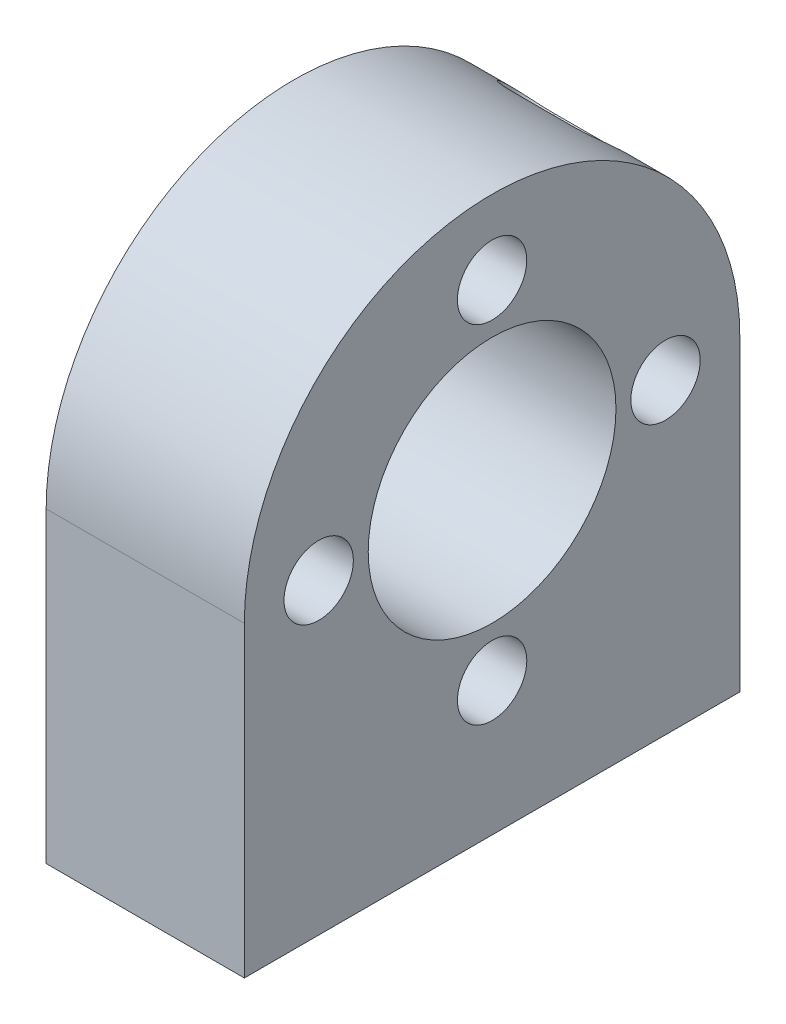
SolidWorks part; units mm, degrees
ref_plane "Ebene vorne" through (0, 0, 0) normal (0, 0, 1) x (1, 0, 0)
ref_plane "Ebene oben" through (0, 0, 0) normal (0, 1, 0) x (1, 0, 0)
ref_plane "Ebene rechts" through (0, 0, 0) normal (1, 0, 0) x (0, 0, -1)
sketch "Skizze1" plane through (0, 0, 0) normal (0, 1, 0) x (1, 0, 0)
  line L1 (-10, -25) -> (10, -25)
  line L2 (-10, -25) -> (-10, 25)
  line L3 (-10, 25) -> (10, 25)
  line L4 (10, -25) -> (10, 25)
  line L5 (-10, -25) -> (10, 25) construction
  line L6 (-10, 25) -> (10, -25) construction
  point P0 (0, 0)
  dimension "D1" = 20
  dimension "D2" = 50
extrude "Aufsatz-Linear austragen1" add sketch "Skizze1" along normal blind 56
sketch "Skizze2" plane through (-10, 0, 0) normal (-1, 0, 0) x (0, 0, 1)
  line L0 (-25, 56) -> (25, 56) construction
  line L1 (-25, 56) -> (-25, 0) construction
  line L2 (25, 56) -> (25, 0) construction
  line L3 (-25, 31) -> (-25, 56)
  line L4 (-25, 56) -> (25, 56)
  line L5 (25, 56) -> (25, 31)
  circle A0 centre (0, 31) radius 25
  circle A1 centre (0, 31) radius 12.5
  circle A2 centre (0, 31) radius 17.5
  circle A3 centre (17.5, 31) radius 2
  circle A4 centre (0, 13.5) radius 2
  circle A5 centre (-17.5, 31) radius 2
  circle A6 centre (0, 48.5) radius 2
  point P15 (0, 31)
  line M7 (25, 0) -> (25, 56)
  line M8 (25, 56) -> (-25, 56)
  line M9 (-25, 56) -> (-25, 0)
  dimension "D1" = 25
  dimension "D2" = 35
  dimension "D3" = 4
extrude "Schnitt-Linear austragen1" cut sketch "Skizze2" against normal through all contours A0 M8 M9 | A0 M7 M8 | A2 A6 | A2 A6 | A2 A5 | A2 A5 | A2 A3 | A2 A3 | A2 A4 | A2 A4 | A1
sketch "Skizze3" plane through (0, 0, 0) normal (0, -1, 0) x (1, 0, 0)
  line L0 (0, 25) -> (0, -25) construction
  line L1 (-10, 25) -> (10, 25) construction
  line L2 (10, -25) -> (-10, -25) construction
  line L4 (0, 0) -> (3.2712, 0) construction
  circle A0 centre (0, 19) radius 1.65
  circle A1 centre (0, 9) radius 1.65
  circle A2 centre (0, -9) radius 1.65
  circle A3 centre (0, -19) radius 1.65
  dimension "D1" = 3.3
  dimension "D2" = 3.3
  dimension "D3" = 6
  dimension "D4" = 10
extrude "Schnitt-Linear austragen2" cut sketch "Skizze3" against normal blind 15 contours A0 | A1 | A2 | A3
sketch "Skizze6" plane through (10, 0, 0) normal (1, 0, 0) x (0, 0, -1)
  circle A0 centre (17.5, 31) radius 3.5
  circle A1 centre (0.0017, 13.4983) radius 3.5
  circle A2 centre (-17.5, 30.9967) radius 3.5
  circle A3 centre (-0.0017, 48.4983) radius 3.5
  point P11 (0, 30.9983)
  dimension "D1" = 7
  dimension "D2" = 4
extrude "Schnitt-Linear austragen5" cut sketch "Skizze6" against normal blind 10 contours A3 | A0 | A1 | A2
ref_plane "Plane1" through (0, 33.1777, -33.1777) normal (0, 0.7071, -0.7071) x (-1, 0, 0)
sketch "Sketch1" plane through (0, 33.1777, -33.1777) normal (0, 0.7071, -0.7071) x (-1, 0, 0)
  line L0 (-3, 22.5) -> (3, 22.5) construction
  line L1 (-3, 25.5) -> (3, 25.5)
  line L2 (-3, 19.5) -> (3, 19.5)
  arc A0 (-3, 25.5) -> (-3, 19.5) centre (-3, 22.5) ccw
  arc A1 (3, 19.5) -> (3, 25.5) centre (3, 22.5) ccw
  point P2 (0, 22.5)
  dimension "D1" = 6
extrude "Cut-Extrude1" cut sketch "Sketch1" against normal blind 17
